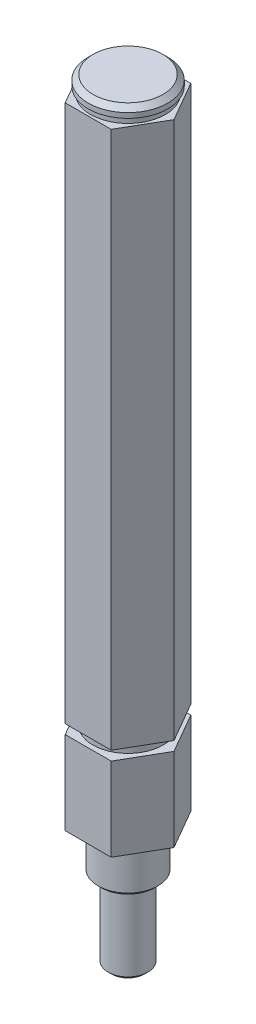
SolidWorks part; units mm, degrees
material "2024-T4"
ref_plane "Front Plane" through (0, 0, 0) normal (0, 0, 1) x (1, 0, 0)
ref_plane "Top Plane" through (0, 0, 0) normal (0, 1, 0) x (1, 0, 0)
ref_plane "Right Plane" through (0, 0, 0) normal (1, 0, 0) x (0, 0, -1)
sketch "Sketch1" plane through (0, 0, 0) normal (0, 1, 0) x (1, 0, 0)
  line L0 (-34.641, 23.019) -> (-41.9733, 23.019)
  line L1 (-41.9733, 23.019) -> (-45.6395, 16.669)
  line L2 (-45.6395, 16.669) -> (-41.9733, 10.319)
  line L3 (-41.9733, 10.319) -> (-34.641, 10.319)
  line L4 (-34.641, 10.319) -> (-30.9748, 16.669)
  line L5 (-30.9748, 16.669) -> (-34.641, 23.019)
extrude "Boss-Extrude1" add sketch "Sketch1" against normal blind 10.6172
sketch "Sketch2" plane through (0, -10.6172, 0) normal (0, -1, 0) x (1, 0, 0)
  circle A0 centre (-38.3071, -16.669) radius 5.588
extrude "Boss-Extrude2" add sketch "Sketch2" along normal blind 1.4986
ref_plane "Plane1" through (0, -12.1158, 0) normal (0, 1, 0) x (-1, 0, 0)
sketch "Sketch3" plane through (0, -12.1158, 0) normal (0, 1, 0) x (-1, 0, 0)
  line L0 (41.9733, -23.019) -> (45.6395, -16.669)
  line L1 (45.6395, -16.669) -> (41.9733, -10.319)
  line L2 (41.9733, -10.319) -> (34.641, -10.319)
  line L3 (34.641, -10.319) -> (30.9748, -16.669)
  line L4 (30.9748, -16.669) -> (34.641, -23.019)
  line L5 (34.641, -23.019) -> (41.9733, -23.019)
extrude "Boss-Extrude3" add sketch "Sketch3" against normal blind 13.2842
sketch "Sketch4" plane through (0, -25.4, 0) normal (0, -1, 0) x (1, 0, 0)
  circle A0 centre (-38.3071, -16.669) radius 4.7498
extrude "Boss-Extrude4" add sketch "Sketch4" along normal blind 7.112
sketch "Sketch5" plane through (0, -32.512, 0) normal (0, -1, 0) x (1, 0, 0)
  circle A0 centre (-38.3071, -16.669) radius 3.1623
sketch "Sketch10" plane through (0, 0, 0) normal (0, 1, 0) x (1, 0, 0)
  line L6 (-30.9748, 16.669) -> (-34.641, 23.019)
  line L7 (-34.641, 23.019) -> (-41.9733, 23.019)
  line L8 (-41.9733, 23.019) -> (-45.6395, 16.669)
  line L9 (-45.6395, 16.669) -> (-41.9733, 10.319)
  line L10 (-41.9733, 10.319) -> (-34.641, 10.319)
  line L11 (-34.641, 10.319) -> (-30.9748, 16.669)
  line L12 (-30.9748, 16.669) -> (-34.641, 23.019)
  line L13 (-34.641, 23.019) -> (-41.9733, 23.019)
  line L14 (-41.9733, 23.019) -> (-45.6395, 16.669)
  line L15 (-45.6395, 16.669) -> (-41.9733, 10.319)
  line L16 (-41.9733, 10.319) -> (-34.641, 10.319)
  line L17 (-34.641, 10.319) -> (-30.9748, 16.669)
  dimension "D1" = 0
extrude "Boss-Extrude7" add sketch "Sketch10" along normal blind 134.62
extrude "Boss-Extrude5" add sketch "Sketch5" along normal blind 12.7
ref_plane "Plane2" through (0, 0, -11.9446) normal (0, 0, -1) x (-1, 0, 0)
chamfer "Chamfer1" distance 0.508 angle 45 1 edges at (-38.3071, -45.212, -19.8313)
chamfer "Chamfer2" distance 0.508 angle 45 1 edges at (-38.3071, -32.512, -21.4188)
sketch "Sketch11" plane through (0, 134.62, 0) normal (0, 1, 0) x (1, 0, 0)
  line L6 (-34.641, 10.319) -> (-30.9748, 16.669)
  line L7 (-30.9748, 16.669) -> (-34.641, 23.019)
  line L8 (-34.641, 23.019) -> (-41.9733, 23.019)
  line L9 (-41.9733, 23.019) -> (-45.6395, 16.669)
  line L10 (-45.6395, 16.669) -> (-41.9733, 10.319)
  line L11 (-41.9733, 10.319) -> (-34.641, 10.319)
  line L12 (-34.641, 10.319) -> (-30.9748, 16.669)
  line L13 (-30.9748, 16.669) -> (-34.641, 23.019)
  line L14 (-34.641, 23.019) -> (-41.9733, 23.019)
  line L15 (-41.9733, 23.019) -> (-45.6395, 16.669)
  line L16 (-45.6395, 16.669) -> (-41.9733, 10.319)
  line L17 (-41.9733, 10.319) -> (-34.641, 10.319)
  dimension "D1" = 0
extrude "Cut-Extrude2" cut sketch "Sketch11" against normal up to surface (59.4614 mm away)
sketch "Sketch12" plane through (0, 75.1586, 0) normal (0, 1, 0) x (1, 0, 0)
  circle A0 centre (-38.3071, 16.669) radius 5.9436
  circle A1 centre (-38.3071, 16.669) radius 3.1623 construction
  dimension "D1" = 11.8872
extrude "Boss-Extrude8" add sketch "Sketch12" along normal blind 0.9906
sketch "Sketch13" plane through (0, 76.1492, 0) normal (0, 1, 0) x (1, 0, 0)
  circle A0 centre (-38.3071, 16.669) radius 6.35
  dimension "D1" = 12.7
extrude "Boss-Extrude9" add sketch "Sketch13" along normal blind 1.5875
chamfer "Chamfer3" distance 0.7937 angle 45 1 edges at (-44.6571, 77.7367, -16.669)
ref_plane "Plane3" through (0, 53.1876, 0) normal (0, 1, 0) x (-1, 0, 0)
